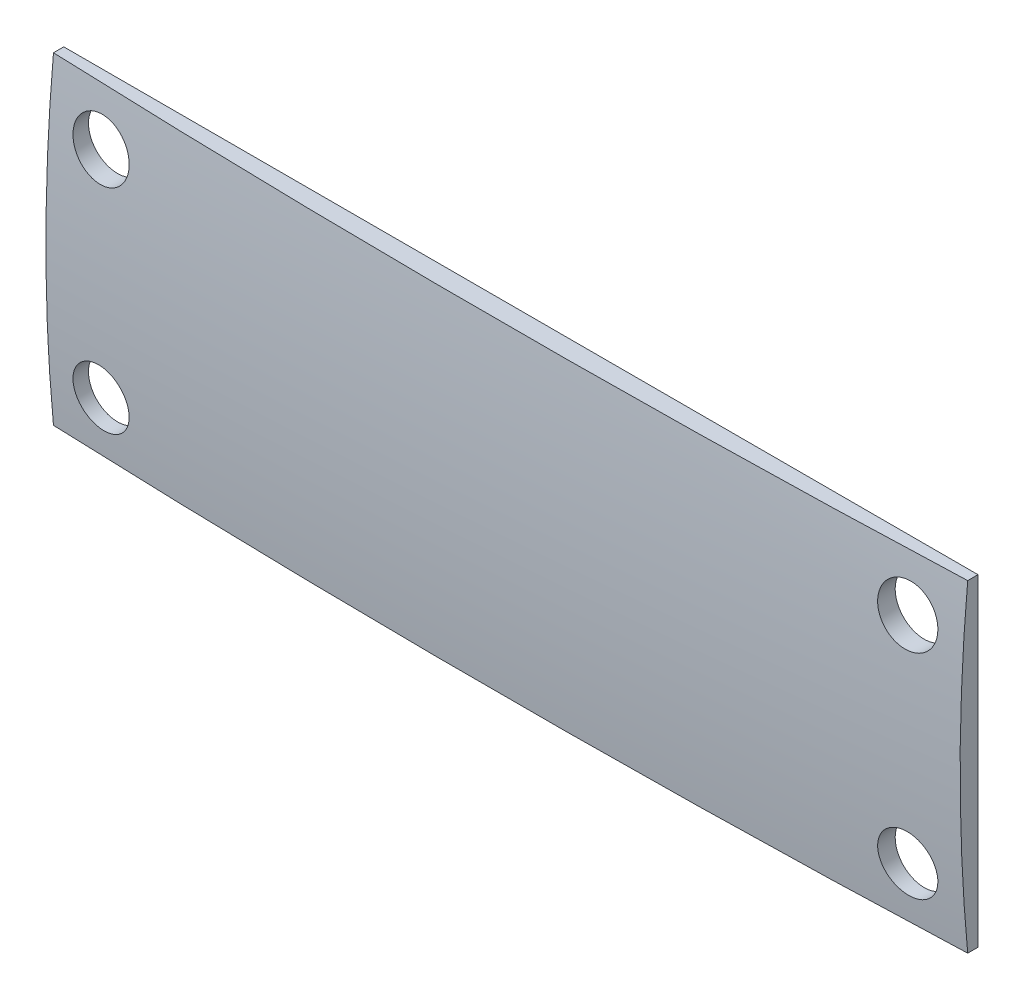
SolidWorks part; units mm, degrees
material "Nylon 101"
ref_plane "Front Plane" through (0, 0, 0) normal (0, 0, 1) x (1, 0, 0)
ref_plane "Top Plane" through (0, 0, 0) normal (0, 1, 0) x (1, 0, 0)
ref_plane "Right Plane" through (0, 0, 0) normal (1, 0, 0) x (0, 0, -1)
sketch "Sketch1" plane through (0, 0, 0) normal (0, 0, 1) x (1, 0, 0)
  line L1 (-53.975, 19.05) -> (53.975, 19.05)
  line L2 (-53.975, 19.05) -> (-53.975, -19.05)
  line L3 (-53.975, -19.05) -> (53.975, -19.05)
  line L4 (53.975, 19.05) -> (53.975, -19.05)
  line L5 (-53.975, 19.05) -> (53.975, -19.05) construction
  line L6 (-53.975, -19.05) -> (53.975, 19.05) construction
  point P0 (0, 0)
  dimension "D1" = 107.95
  dimension "D2" = 38.1
sketch "Sketch2" plane through (0, 0, 0) normal (1, 0, 0) x (0, 0, -1)
  line L0 (1372.87, -527.05) -> (1372.87, 527.05)
  ellipse E0 centre (1372.87, 0) end of major axis (0, 0) minor radius 527.05 (1372.87, 527.05) -> (1372.87, -527.05) ccw
revolve "Revolve1" add sketch "Sketch2" angle 360 about L0
extrude "Cut-Extrude1" cut sketch "Sketch1" against normal through all flip side to cut
sketch "Sketch3" plane through (0, 0, 0) normal (0, 0, 1) x (1, 0, 0)
  line L1 (53.975, 22.3762) -> (-53.975, 22.3762)
  line L2 (53.975, 22.3762) -> (53.975, -22.3762)
  line L3 (53.975, -22.3762) -> (-53.975, -22.3762)
  line L4 (-53.975, 22.3762) -> (-53.975, -22.3762)
  line L5 (53.975, 22.3762) -> (-53.975, -22.3762) construction
  line L6 (53.975, -22.3762) -> (-53.975, 22.3762) construction
  point P0 (0, 0)
  dimension "D1" = 107.95
extrude "Cut-Extrude2" cut sketch "Sketch3" against normal through all from offset 3.175 offset against normal yes
sketch "Sketch4" plane through (0, 0, -3.175) normal (0, 0, -1) x (-1, 0, 0)
  line L0 (53.975, 19.05) -> (53.975, -19.05) construction
  line L1 (-53.975, -19.05) -> (-53.975, 19.05) construction
  line L2 (-53.975, 19.05) -> (53.975, 19.05) construction
  line L3 (53.975, -19.05) -> (-53.975, -19.05) construction
  circle A0 centre (-47.625, -12.7) radius 3.429
  circle A1 centre (-47.625, 12.7) radius 3.429
  circle A2 centre (47.625, 12.7) radius 3.429
  circle A3 centre (47.625, -12.7) radius 3.429
  dimension "D1" = 6.858
  dimension "D2" = 6.35
  dimension "D3" = 6.35
  dimension "D4" = 6.35
  dimension "D5" = 6.35
extrude "Cut-Extrude3" cut sketch "Sketch4" against normal through all both and the other way through all
